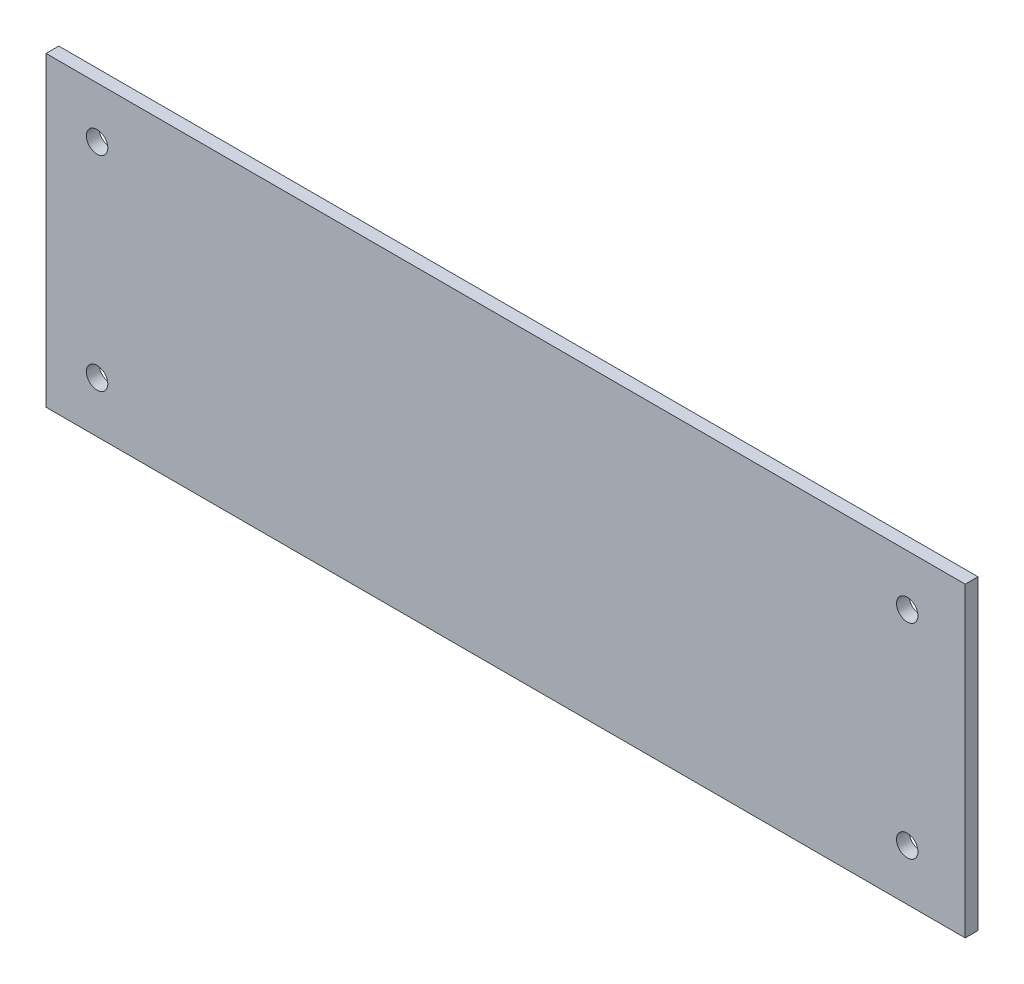
SolidWorks part; units mm, degrees
ref_plane "Front Plane" through (0, 0, 0) normal (0, 0, 1) x (1, 0, 0)
ref_plane "Top Plane" through (0, 0, 0) normal (0, 1, 0) x (1, 0, 0)
ref_plane "Right Plane" through (0, 0, 0) normal (1, 0, 0) x (0, 0, -1)
sketch "Sketch1" plane through (0, 0, 0) normal (0, 0, 1) x (1, 0, 0)
  line L1 (-114.3, 38.1) -> (114.3, 38.1)
  line L2 (-114.3, 38.1) -> (-114.3, -38.1)
  line L3 (-114.3, -38.1) -> (114.3, -38.1)
  line L4 (114.3, 38.1) -> (114.3, -38.1)
  line L5 (-114.3, 38.1) -> (114.3, -38.1) construction
  line L6 (-114.3, -38.1) -> (114.3, 38.1) construction
  point P0 (0, 0)
extrude "Boss-Extrude1" add sketch "Sketch1" along normal blind 3.175
sketch "Sketch3" plane through (0, 0, 3.175) normal (0, 0, 1) x (1, 0, 0)
  line L2 (-114.3, 25.4) -> (-101.6, 25.4) construction
  line L3 (-114.3, 38.1) -> (-114.3, -38.1) construction
  line L4 (-101.6, 25.4) -> (-101.6, 38.1) construction
  line L5 (114.3, 38.1) -> (-114.3, 38.1) construction
  line L6 (-114.3, 0) -> (114.3, 0) construction
  line L7 (114.3, -38.1) -> (114.3, 38.1) construction
  line L8 (-0.8637, 38.1) -> (-0.8637, -38.1) construction
  line L9 (-114.3, -38.1) -> (114.3, -38.1) construction
  circle A1 centre (-101.6, 25.4) radius 2.667
  circle A2 centre (-101.6, -25.4) radius 2.667
  circle A3 centre (99.8726, -25.4) radius 2.667
  circle A4 centre (99.8726, 25.4) radius 2.667
  dimension "D1" = 12.7
  dimension "D2" = 12.7
extrude "Cut-Extrude2" cut sketch "Sketch3" against normal blind 3.175
